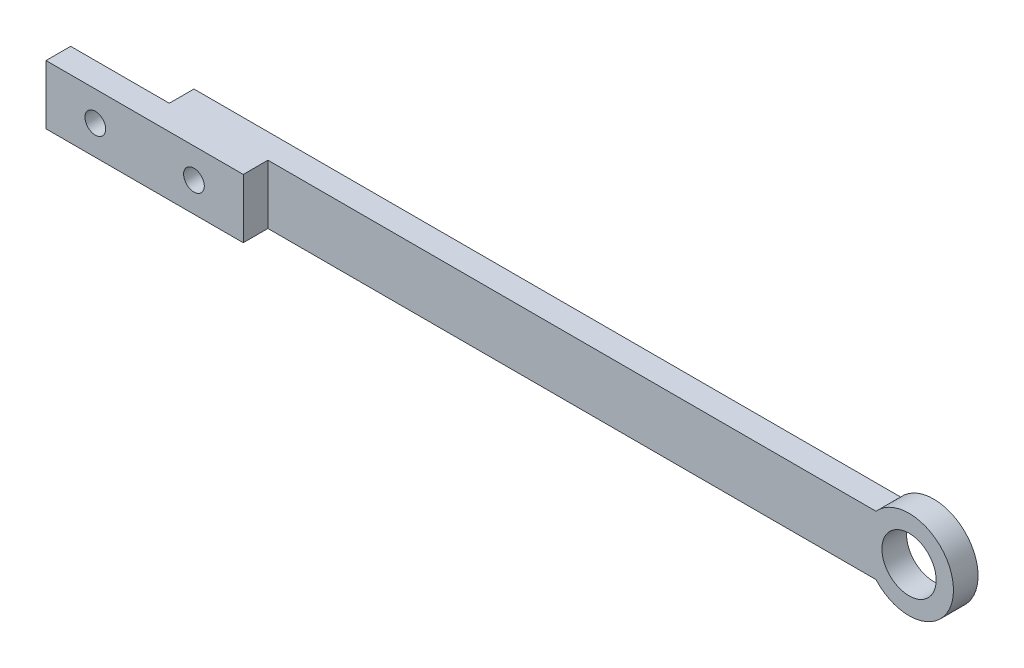
SolidWorks part; units mm, degrees
ref_plane "Front Plane" through (0, 0, 0) normal (0, 0, 1) x (1, 0, 0)
ref_plane "Top Plane" through (0, 0, 0) normal (0, 1, 0) x (1, 0, 0)
ref_plane "Right Plane" through (0, 0, 0) normal (1, 0, 0) x (0, 0, -1)
sketch "Sketch1" plane through (0, 0, 0) normal (0, 0, 1) x (1, 0, 0)
  line L0 (-6.7082, 6) -> (-150, 6)
  line L1 (-150, 6) -> (-150, -6)
  line L2 (-150, -6) -> (-6.7082, -6)
  arc A0 (-6.7082, -6) -> (-6.7082, 6) centre (0, 0) ccw
  dimension "D1" = 18
  dimension "D2" = 6
  dimension "D3" = 150
extrude "Boss-Extrude1" add sketch "Sketch1" along normal blind 5
sketch "Sketch2" plane through (0, 0, 5) normal (0, 0, 1) x (1, 0, 0)
  circle A0 centre (0, 0) radius 5.5
  dimension "D1" = 11
extrude "Cut-Extrude1" cut sketch "Sketch2" against normal through all
sketch "Sketch3" plane through (0, 0, 5) normal (0, 0, 1) x (1, 0, 0)
  line L0 (-6.7082, 6) -> (-150, 6) construction
  line L1 (-130, 6) -> (-170, 6)
  line L2 (-130, 6) -> (-130, -6)
  line L3 (-130, -6) -> (-170, -6)
  line L4 (-170, 6) -> (-170, -6)
  line L5 (-150, -6) -> (-6.7082, -6) construction
  line L6 (-150, 6) -> (-150, -6) construction
  dimension "D1" = 20
  dimension "D2" = 20
extrude "Boss-Extrude2" add sketch "Sketch3" along normal blind 5
sketch "Sketch4" plane through (0, 0, 10) normal (0, 0, 1) x (1, 0, 0)
  line L0 (-170, 6) -> (-170, -6) construction
  circle A0 centre (-160, 0) radius 2.1
  circle A1 centre (-140, 0) radius 2.1
  dimension "D1" = 4.2
  dimension "D2" = 10
  dimension "D3" = 20
extrude "Cut-Extrude2" cut sketch "Sketch4" against normal through all
